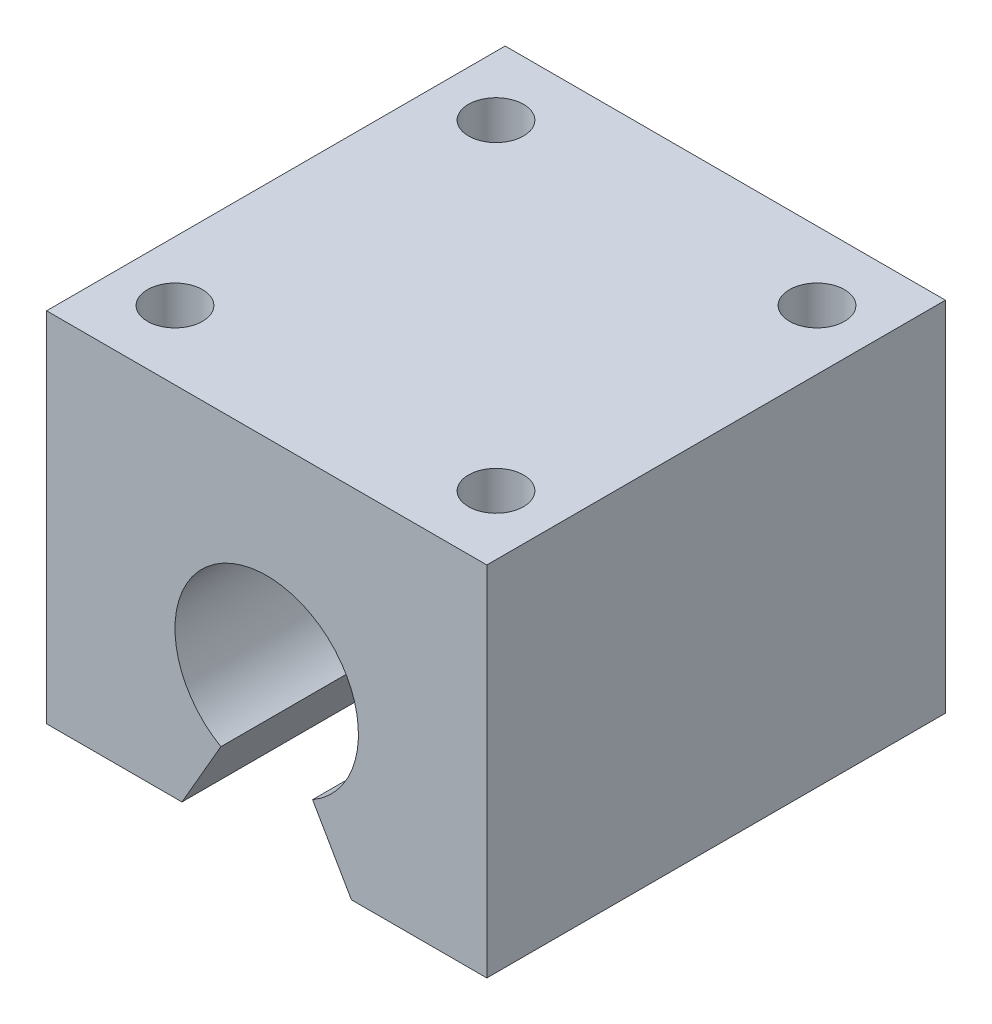
SolidWorks part; units mm, degrees
ref_plane "Front Plane" through (0, 0, 0) normal (0, 0, 1) x (1, 0, 0)
ref_plane "Top Plane" through (0, 0, 0) normal (0, 1, 0) x (1, 0, 0)
ref_plane "Right Plane" through (0, 0, 0) normal (1, 0, 0) x (0, 0, -1)
sketch "Sketch1" plane through (0, 0, 0) normal (0, 0, 1) x (1, 0, 0)
  line L0 (0, 37.5782) -> (0, -32.8933) construction
  line L1 (-24, 23) -> (24, 23)
  line L2 (-24, 23) -> (-24, -16)
  line L3 (-24, -16) -> (-9.2376, -16)
  line L4 (24, 23) -> (24, -16)
  line L5 (-24, 23) -> (24, -16) construction
  line L6 (-24, -16) -> (24, 23) construction
  line L7 (5, -8.6603) -> (9.2376, -16)
  line L8 (-5, -8.6603) -> (-9.2376, -16)
  line L9 (9.2376, -16) -> (24, -16)
  line L10 (-33.9516, 0) -> (37.6079, 0) construction
  arc A0 (5, -8.6603) -> (-5, -8.6603) centre (0, 0) ccw
  point P3 (0, 3.5)
  dimension "D1" = 20
  dimension "D2" = 30
  dimension "D3" = 60
  dimension "D4" = 10
  dimension "D5" = 23
  dimension "D6" = 39
  dimension "D7" = 48
extrude "Boss-Extrude1" add sketch "Sketch1" along normal mid plane 50
sketch "Sketch2" plane through (0, 23, 0) normal (0, 1, 0) x (1, 0, 0)
  line L1 (-17.5, 17.5) -> (17.5, 17.5) construction
  line L2 (-17.5, 17.5) -> (-17.5, -17.5) construction
  line L3 (-17.5, -17.5) -> (17.5, -17.5) construction
  line L4 (17.5, 17.5) -> (17.5, -17.5) construction
  line L5 (-17.5, 17.5) -> (17.5, -17.5) construction
  line L6 (-17.5, -17.5) -> (17.5, 17.5) construction
  circle A0 centre (-17.5, 17.5) radius 3
  circle A1 centre (17.5, 17.5) radius 3
  circle A2 centre (17.5, -17.5) radius 3
  circle A3 centre (-17.5, -17.5) radius 3
  point P0 (0, 0)
  dimension "D3" = 6
  dimension "D1" = 35
  dimension "D2" = 35
extrude "Cut-Extrude1" cut sketch "Sketch2" against normal blind 11
